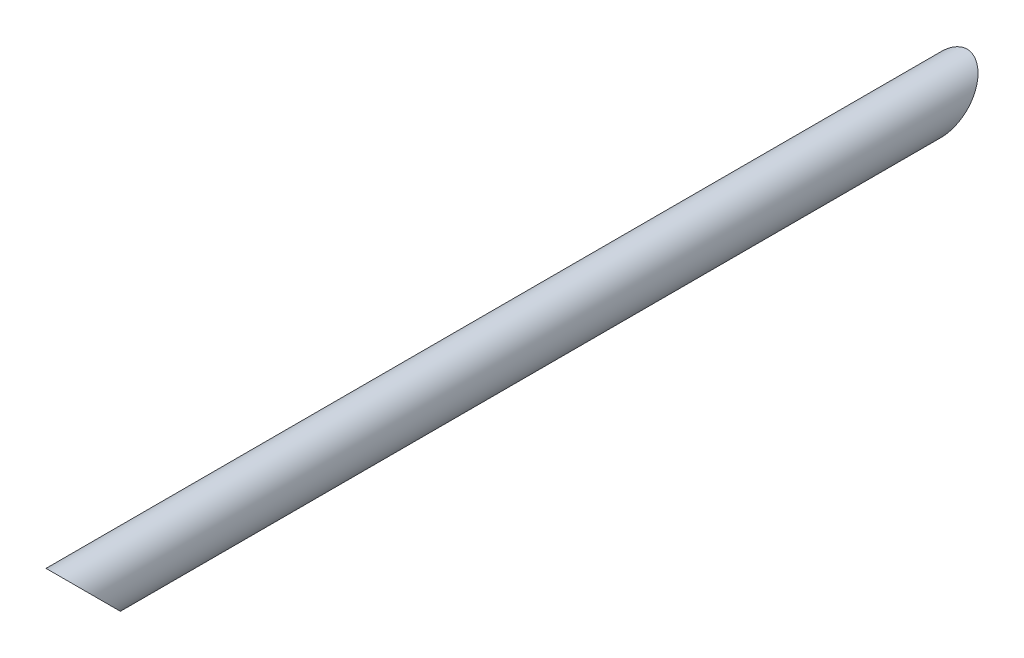
SolidWorks part; units mm, degrees
ref_plane "Front Plane" through (0, 0, 0) normal (0, 0, 1) x (1, 0, 0)
ref_plane "Top Plane" through (0, 0, 0) normal (0, 1, 0) x (1, 0, 0)
ref_plane "Right Plane" through (0, 0, 0) normal (1, 0, 0) x (0, 0, -1)
sketch "Sketch1" plane through (0, 0, 0) normal (0, 0, 1) x (1, 0, 0)
  circle A0 centre (0, 0) radius 26.9875
  dimension "D1" = 53.975
extrude "Boss-Extrude1" add sketch "Sketch1" along normal blind 933.45 contours A0
sketch "Sketch2" plane through (0, 0, 0) normal (1, 0, 0) x (0, 0, -1)
  line L0 (-933.45, 26.9875) -> (-879.475, -26.9875)
  line L1 (0, 26.9875) -> (-933.45, 26.9875) construction
  line L2 (-933.45, 26.9875) -> (-933.45, -26.9875) construction
  line L3 (-933.45, -26.9875) -> (0, -26.9875) construction
  line L4 (-933.45, -26.9875) -> (-879.475, -26.9875)
  line L5 (-933.45, 26.9875) -> (-933.45, -26.9875)
  line L6 (0, 26.9875) -> (-53.975, -26.9875)
  line L7 (-53.975, -26.9875) -> (0, -26.9875)
  line L8 (0, -26.9875) -> (0, 26.9875)
extrude "Cut-Extrude2" cut sketch "Sketch2" against normal through all both and the other way through all
ref_plane "Plane1" through (0, 0, 466.725) normal (0, 0, -1) x (-1, 0, 0)
